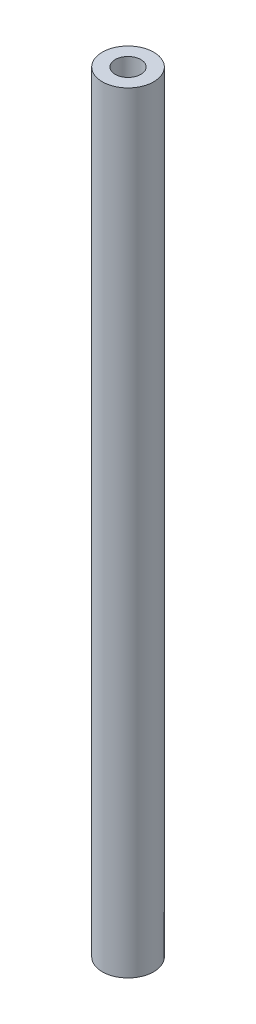
SolidWorks part; units mm, degrees
ref_plane "前视基准面" through (0, 0, 0) normal (0, 0, 1) x (1, 0, 0)
ref_plane "上视基准面" through (0, 0, 0) normal (0, 1, 0) x (1, 0, 0)
ref_plane "右视基准面" through (0, 0, 0) normal (1, 0, 0) x (0, 0, -1)
sketch "草图1" plane through (0, 0, 0) normal (0, 1, 0) x (1, 0, 0)
  circle A0 centre (0, 0) radius 1.5
  circle A1 centre (0, 0) radius 3
  point P5 (0, 0)
  dimension "D1" = 6
  dimension "D2" = 3
extrude "凸台-拉伸1" add sketch "草图1" along normal blind 90
